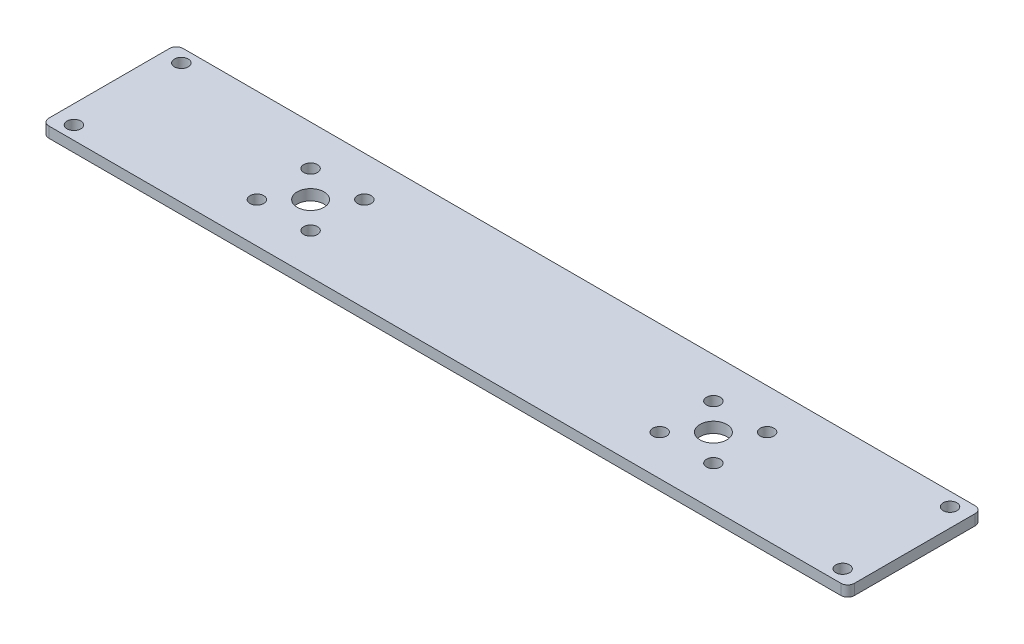
SolidWorks part; units mm, degrees
ref_plane "Front Plane" through (0, 0, 0) normal (0, 0, 1) x (1, 0, 0)
ref_plane "Top Plane" through (0, 0, 0) normal (0, 1, 0) x (1, 0, 0)
ref_plane "Right Plane" through (0, 0, 0) normal (1, 0, 0) x (0, 0, -1)
sketch "Sketch1" plane through (0, 0, 0) normal (0, 1, 0) x (1, 0, 0)
  line L0 (2.396, 0) -> (50002.396, 0) construction
  line L1 (-120, -20) -> (120, -20)
  line L2 (-120, -20) -> (-120, 20)
  line L3 (-120, 20) -> (120, 20)
  line L4 (120, -20) -> (120, 20)
  line L5 (-120, -20) -> (120, 20) construction
  line L6 (-120, 20) -> (120, -20) construction
  line L7 (114.5, 16) -> (-114.5, 16) construction
  line L8 (114.5, 16) -> (114.5, -16) construction
  line L9 (114.5, -16) -> (-114.5, -16) construction
  line L10 (-114.5, 16) -> (-114.5, -16) construction
  line L11 (114.5, 16) -> (-114.5, -16) construction
  line L12 (114.5, -16) -> (-114.5, 16) construction
  line L13 (0, -0.0286) -> (0, -50000.0286) construction
  line L14 (-68, 8) -> (-52, 8) construction
  line L15 (-68, 8) -> (-68, -8) construction
  line L16 (-68, -8) -> (-52, -8) construction
  line L17 (-52, 8) -> (-52, -8) construction
  line L18 (-68, 8) -> (-52, -8) construction
  line L19 (-68, -8) -> (-52, 8) construction
  circle A0 centre (114.5, 16) radius 2.05
  circle A1 centre (114.5, -16) radius 2.05
  circle A2 centre (-114.5, 16) radius 2.05
  circle A3 centre (-114.5, -16) radius 2.05
  circle A4 centre (-52, -8) radius 2.05
  circle A5 centre (-68, -8) radius 2.05
  circle A6 centre (-68, 8) radius 2.05
  circle A7 centre (-52, 8) radius 2.05
  circle A8 centre (-60, 0) radius 4
  circle A9 centre (68, 8) radius 2.05
  circle A10 centre (52, 8) radius 2.05
  circle A11 centre (60, 0) radius 4
  circle A12 centre (68, -8) radius 2.05
  circle A13 centre (52, -8) radius 2.05
  point P0 (0, 0)
  point P6 (0, 0)
  point P17 (-60, 0)
  dimension "D5" = 4.1
  dimension "D9" = 8
  dimension "D1" = 240
  dimension "D2" = 40
  dimension "D3" = 32
  dimension "D4" = 229
  dimension "D6" = 16
  dimension "D7" = 16
  dimension "D8" = 60
extrude "Boss-Extrude1" add sketch "Sketch1" along normal blind 3.175
fillet "Fillet1" radius 2 4 edges at (-120, 1.5875, 20) (-120, 1.5875, -20) (120, 1.5875, -20) (120, 1.5875, 20)
